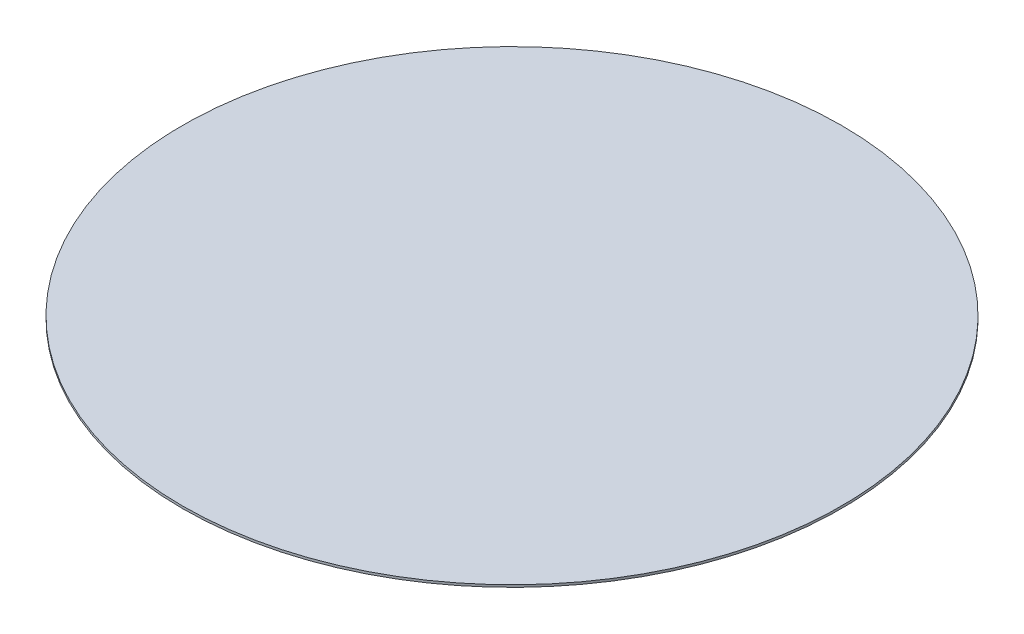
SolidWorks part; units mm, degrees
material "6061"
ref_plane "Front" through (0, 0, 0) normal (0, 0, 1) x (1, 0, 0)
ref_plane "Top" through (0, 0, 0) normal (0, 1, 0) x (1, 0, 0)
ref_plane "Right" through (0, 0, 0) normal (1, 0, 0) x (0, 0, -1)
sketch "Sketch1" plane through (0, 0, 0) normal (0, 1, 0) x (1, 0, 0)
  circle A0 centre (0, 0) radius 100
  dimension "D1" = 200
extrude "Boss-Extrude1" add sketch "Sketch1" along normal blind 0.7
